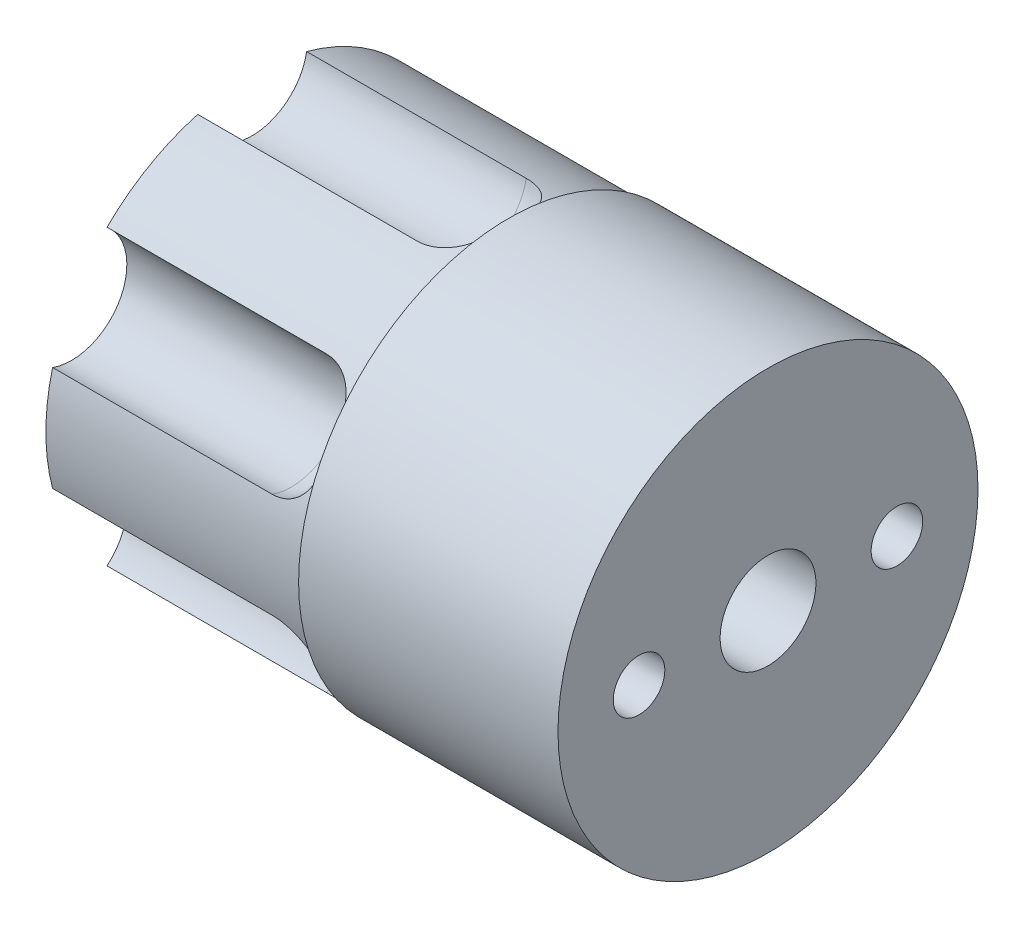
SolidWorks part; units mm, degrees
ref_plane "Спереди" through (0, 0, 0) normal (0, 0, 1) x (1, 0, 0)
ref_plane "Сверху" through (0, 0, 0) normal (0, 1, 0) x (1, 0, 0)
ref_plane "Справа" through (0, 0, 0) normal (1, 0, 0) x (0, 0, -1)
sketch "Эскиз1" plane through (0, 0, 0) normal (0, 0, 1) x (1, 0, 0)
  line L0 (-15.7098, 0) -> (38.8611, 0) construction
  line L1 (0, 6.5) -> (15.2, 6.5)
  line L2 (15.2, 6.5) -> (15.2, 9.5)
  line L3 (15.2, 9.5) -> (4.7, 9.5)
  line L4 (4.7, 9.5) -> (4.7, 17.5)
  line L5 (4.7, 17.5) -> (35.2, 17.5)
  line L6 (35.2, 17.5) -> (35.2, 22.5)
  line L7 (35.2, 22.5) -> (55, 22.5)
  line L11 (70, 28.5) -> (34.8, 28.5)
  line L12 (34.8, 28.5) -> (34.8, 28)
  line L13 (34.8, 28) -> (0, 28)
  line L14 (0, 28) -> (0, 6.5)
  line L15 (70, 28.5) -> (70, 6.5)
  line L16 (70, 6.5) -> (55, 6.5)
  line L17 (55, 6.5) -> (55, 22.5)
  dimension "D1" = 15.2
  dimension "D2" = 6.5
  dimension "D3" = 3
  dimension "D4" = 10.5
  dimension "D5" = 17.5
  dimension "D6" = 5
  dimension "D8" = 28.5
  dimension "D10" = 35.2
  dimension "D11" = 0.5
  dimension "D12" = 34.8
  dimension "D13" = 30.5
  dimension "D14" = 22
  dimension "D15" = 15
revolve "Повернуть1" add sketch "Эскиз1" angle 360 about L0
sketch "Эскиз2" plane through (0, 0, 0) normal (-1, 0, 0) x (0, 0, 1)
  arc A0 (-7.5, 28.2721) -> (7.5, 28.2721) centre (0, 28.3001) ccw
  arc A2 (20.7344, 20.6312) -> (28.2344, 7.6409) centre (24.5086, 14.15) ccw
  arc A3 (28.2344, -7.6409) -> (20.7344, -20.6312) centre (24.5086, -14.15) ccw
  arc A4 (7.5, -28.2721) -> (-7.5, -28.2721) centre (0, -28.3001) ccw
  arc A5 (-20.7344, -20.6312) -> (-28.2344, -7.6409) centre (-24.5086, -14.15) ccw
  arc A6 (-28.2344, 7.6409) -> (-20.7344, 20.6312) centre (-24.5086, 14.15) ccw
  arc A7 (-7.5, 28.2721) -> (7.5, 28.2721) centre (0, 0) cw
  arc A8 (20.7344, 20.6312) -> (28.2344, 7.6409) centre (0, 0) cw
  arc A9 (28.2344, -7.6409) -> (20.7344, -20.6312) centre (0, 0) cw
  arc A10 (7.5, -28.2721) -> (-7.5, -28.2721) centre (0, 0) cw
  arc A11 (-20.7344, -20.6312) -> (-28.2344, -7.6409) centre (0, 0) cw
  arc A12 (-28.2344, 7.6409) -> (-20.7344, 20.6312) centre (0, 0) cw
  circle A17 centre (0, 0) radius 28 construction
  point P23 (0, 0)
  point P35 (0, 0)
  dimension "D2" = 29.25
  dimension "D5" = 7.2
  dimension "D1" = 15
  dimension "D3" = 6
  dimension "D4" = 6
extrude "Вырез-Вытянуть1" cut sketch "Эскиз2" against normal blind 34.8
fillet "Скругление1" radius 5 6 edges at (34.8, 10.4, -18.0133) (34.8, 20.8, 0) (34.8, 10.4, 18.0133) (34.8, -10.4, 18.0133) (34.8, -20.8, 0) (34.8, -10.4, -18.0133)
sketch "Эскиз3" plane through (70, 0, 0) normal (1, 0, 0) x (0, 0, -1)
  line L0 (0, 0) -> (0, 4.2168) construction
  circle A0 centre (-17.5, 0) radius 3.5
  circle A1 centre (17.5, 0) radius 3.5
  dimension "D1" = 35
  dimension "D2" = 7
extrude "Вырез-Вытянуть2" cut sketch "Эскиз3" against normal up to next
